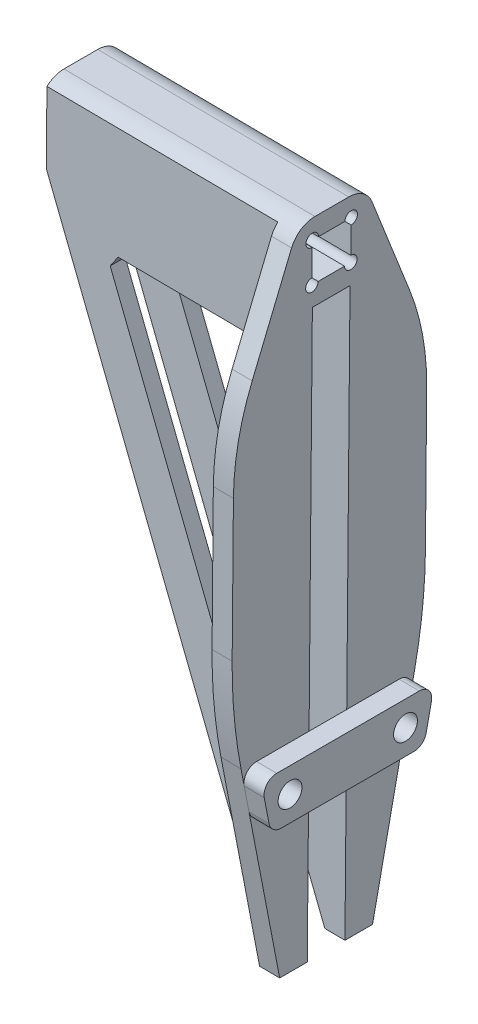
SolidWorks part; units mm, degrees
material "Onyx (Density Only)"
ref_plane "Front Plane" through (0, 0, 0) normal (0, 0, 1) x (1, 0, 0)
ref_plane "Top Plane" through (0, 0, 0) normal (0, 1, 0) x (1, 0, 0)
ref_plane "Right Plane" through (0, 0, 0) normal (1, 0, 0) x (0, 0, -1)
sketch "Sketch1" plane through (0, 0, 0) normal (0, 0, 1) x (1, 0, 0)
  line L0 (-62.6619, -20.8427) -> (-62.2163, 29.2053) construction
  line L1 (-354.9943, -0.7157) -> (-354.7319, 28.7594) construction
  line L2 (-269.9976, -1.4725) -> (-354.9943, -0.7157) construction
  line L3 (-269.9976, -1.4725) -> (-269.7352, 28.0027) construction
  line L4 (-322.9314, 6.2004) -> (-301.9323, 6.0134)
  line L5 (-301.9323, 6.0134) -> (-301.7693, 24.3127)
  line L6 (-301.7693, 24.3127) -> (-322.7685, 24.4997)
  line L7 (-322.7685, 24.4997) -> (-322.9314, 6.2004)
  line L8 (-322.9314, 6.2004) -> (-301.9323, 6.0134)
  line L9 (-301.9323, 6.0134) -> (-301.7693, 24.3127)
  line L10 (-301.7693, 24.3127) -> (-322.7685, 24.4997)
  line L11 (-322.7685, 24.4997) -> (-322.9314, 6.2004)
  line L12 (-371.7271, 31.9358) -> (-371.7538, 28.9359)
  line L13 (-82.6905, -23.6645) -> (-52.6917, -23.9316)
  line L14 (-52.6917, -23.9316) -> (-52.2466, 26.0664)
  line L15 (-52.2466, 26.0664) -> (-371.754, 28.9109)
  line L16 (-386.1059, -102.4513) -> (-381.2798, -121.0102)
  line L17 (-381.2798, -121.0102) -> (-173.5772, -122.8594)
  line L18 (-82.6905, -23.6645) -> (-52.6917, -23.9316)
  line L19 (-52.6917, -23.9316) -> (-52.2466, 26.0664)
  line L20 (-52.2466, 26.0664) -> (-371.754, 28.9109)
  line L21 (-386.1059, -102.4513) -> (-381.2798, -121.0102)
  line L22 (-381.2798, -121.0102) -> (-173.5772, -122.8594)
  line L23 (-371.7538, 28.9359) -> (-39.2441, 25.9756)
  line L24 (-39.2441, 25.9756) -> (-39.2174, 28.9755)
  line L25 (-39.2174, 28.9755) -> (-371.7271, 31.9358)
  line L26 (-371.7271, 31.9358) -> (-371.7538, 28.9359)
  line L27 (-371.7538, 28.9359) -> (-39.2441, 25.9756)
  line L28 (-39.2441, 25.9756) -> (-39.2174, 28.9755)
  line L29 (-39.2174, 28.9755) -> (-371.7271, 31.9358)
  line L30 (-62.6619, -20.8427) -> (-62.2163, 29.2053)
  line L31 (-354.9943, -0.7157) -> (-354.7319, 28.7594)
  line L32 (-269.9976, -1.4725) -> (-354.9943, -0.7157)
  line L33 (-269.9976, -1.4725) -> (-269.7352, 28.0027)
  spline S2 degree 3 poles (2410.225, -2834.3979) (-3146.448, 3563.7765) (2149.655, -3851.3111) (-2597.6592, 3230.2911) knots -1.52414 -1.52414 -1.52414 -1.52414 2.993571 2.993571 2.993571 2.993571 only from (-371.754, 28.9109) to (-386.1059, -102.4513)
  spline S3 degree 3 poles (-3364.9121, 2272.6683) (2814.1163, -2932.1633) (-3073.4881, 2782.8746) (3112.8833, -2413.4756) knots -2.734847 -2.734847 -2.734847 -2.734847 3.726468 3.726468 3.726468 3.726468 only from (-173.5772, -122.8594) to (-82.6905, -23.6645)
  spline S4 degree 3 poles (-371.754, 28.9109) (-424.0354, 24.6168) (-396.3089, -63.2154) (-386.1059, -102.4513) knots 0.202862 0.202862 0.202862 0.202862 0.957857 0.957857 0.957857 0.957857
  spline S5 degree 3 poles (-173.5772, -122.8594) (-128.8291, -103.0455) (-128.3643, -43.0034) (-82.6905, -23.6645) knots 0 0 0 0 1 1 1 1
  dimension "D1" = 0
  dimension "D2" = 0
  dimension "D3" = 0
sketch "Sketch2" plane through (0, 0, 0) normal (0, 0, 1) x (1, 0, 0)
  line L0 (-62.6619, -20.8427) -> (-62.2163, 29.2053) construction
  line L1 (-354.9943, -0.7157) -> (-354.7319, 28.7594) construction
  line L2 (-269.9976, -1.4725) -> (-354.9943, -0.7157) construction
  line L3 (-269.9976, -1.4725) -> (-269.7352, 28.0027) construction
  line L4 (-322.9314, 6.2004) -> (-301.9323, 6.0134)
  line L5 (-82.6905, -23.6645) -> (-52.6917, -23.9316)
  line L6 (-52.6917, -23.9316) -> (-52.2466, 26.0664)
  line L7 (-52.2466, 26.0664) -> (-371.754, 28.9109)
  line L8 (-386.1059, -102.4513) -> (-381.2798, -121.0102)
  line L9 (-381.2798, -121.0102) -> (-173.5772, -122.8594)
  line L10 (-82.6905, -23.6645) -> (-52.6917, -23.9316) construction
  line L11 (-52.6917, -23.9316) -> (-52.2466, 26.0664) construction
  line L12 (-52.2466, 26.0664) -> (-371.754, 28.9109) construction
  line L13 (-386.1059, -102.4513) -> (-381.2798, -121.0102) construction
  line L14 (-381.2798, -121.0102) -> (-173.5772, -122.8594) construction
  line L15 (-301.9323, 6.0134) -> (-301.7693, 24.3127)
  line L16 (-301.7693, 24.3127) -> (-322.7685, 24.4997)
  line L17 (-322.7685, 24.4997) -> (-322.9314, 6.2004)
  line L18 (-322.9314, 6.2004) -> (-301.9323, 6.0134) construction
  line L19 (-301.9323, 6.0134) -> (-301.7693, 24.3127) construction
  line L20 (-301.7693, 24.3127) -> (-322.7685, 24.4997) construction
  line L21 (-322.7685, 24.4997) -> (-322.9314, 6.2004) construction
  line L22 (-39.2441, 25.9756) -> (-39.2174, 28.9755)
  line L23 (-371.7538, 28.9359) -> (-39.2441, 25.9756)
  line L24 (-371.7271, 31.9358) -> (-371.7538, 28.9359)
  line L25 (-39.2174, 28.9755) -> (-371.7271, 31.9358)
  line L26 (-39.2441, 25.9756) -> (-39.2174, 28.9755) construction
  line L27 (-371.7538, 28.9359) -> (-39.2441, 25.9756) construction
  line L28 (-371.7271, 31.9358) -> (-371.7538, 28.9359) construction
  line L29 (-39.2174, 28.9755) -> (-371.7271, 31.9358) construction
  line L30 (-62.6619, -20.8427) -> (-62.2163, 29.2053) construction
  line L31 (-354.9943, -0.7157) -> (-354.7319, 28.7594) construction
  line L32 (-269.9976, -1.4725) -> (-354.9943, -0.7157) construction
  line L33 (-269.9976, -1.4725) -> (-269.7352, 28.0027) construction
  line L34 (-159.2127, 30.0438) -> (-159.6578, -19.9562)
  spline S2 degree 3 poles (3711.5688, -4352.7198) (-4405.7996, 5221.6724) (3347.4946, -5555.5394) (-3714.769, 4889.0268) knots -1.833594 -1.833594 -1.833594 -1.833594 3.301446 3.301446 3.301446 3.301446 only from (-371.754, 28.9109) to (-386.1059, -102.4513)
  spline S3 degree 3 poles (-4888.4094, 3568.1658) (4295.8794, -4300.758) (-4555.8185, 4150.8213) (4638.0833, -3707.0277) knots -3.19796 -3.19796 -3.19796 -3.19796 4.189584 4.189584 4.189584 4.189584 only from (-173.5772, -122.8594) to (-82.6905, -23.6645)
  spline S4 degree 3 poles (-371.754, 28.9109) (-424.0354, 24.6168) (-396.3089, -63.2154) (-386.1059, -102.4513) knots 0.202862 0.202862 0.202862 0.202862 0.957857 0.957857 0.957857 0.957857 construction
  spline S5 degree 3 poles (-173.5772, -122.8594) (-128.8291, -103.0455) (-128.3643, -43.0034) (-82.6905, -23.6645) knots 0 0 0 0 1 1 1 1 construction
  dimension "D4" = 120
  dimension "D5" = 50
  dimension "D1" = 0
  dimension "D2" = 0
  dimension "D3" = 0
sketch "Sketch3" plane through (0, 0, 0) normal (0, 0, 1) x (1, 0, 0)
  line L0 (-159.2127, 30.0438) -> (-159.6578, -19.9562) construction
  line L1 (-159.2127, 30.0438) -> (-159.6578, -19.9562)
  line L2 (-169.2123, 30.1329) -> (-169.6574, -19.8671)
  line L3 (-149.2131, 29.9548) -> (-149.6582, -20.0452)
  line L4 (-149.2131, 29.9548) -> (-169.2123, 30.1329)
  line L5 (-149.6582, -20.0452) -> (-169.6574, -19.8671)
  line L6 (-149.2131, 29.9548) -> (-149.1988, 31.5547)
  line L7 (-149.1988, 31.5547) -> (-169.198, 31.7328)
  line L8 (-169.198, 31.7328) -> (-169.2123, 30.1329)
  dimension "D3" = 1.6
  dimension "D1" = 10
  dimension "D2" = 10
extrude "Boss-Extrude1" add sketch "Sketch3" along normal mid plane 3 contours L5 L3 L4 L1 | L5 L1 L4 L2 | L7 L8 L4 L6
sketch "Sketch4" plane through (0, 0, 0) normal (0, 0, 1) x (1, 0, 0)
  line L0 (-169.2123, 30.1329) -> (-169.6574, -19.8671) construction
  line L1 (-149.6582, -20.0452) -> (-169.6574, -19.8671) construction
  line L2 (-149.2131, 29.9548) -> (-149.6582, -20.0452) construction
  line L3 (-149.2131, 29.9548) -> (-169.2123, 30.1329) construction
  line L4 (-149.2131, 29.9548) -> (-149.1988, 31.5547) construction
  line L5 (-149.1988, 31.5547) -> (-169.198, 31.7328) construction
  line L6 (-169.198, 31.7328) -> (-169.2123, 30.1329) construction
  line L7 (-159.2127, 30.0438) -> (-159.6578, -19.9562) construction
  line L8 (-169.2123, 30.1329) -> (-169.6574, -19.8671)
  line L9 (-149.6582, -20.0452) -> (-169.6574, -19.8671)
  line L10 (-149.2131, 29.9548) -> (-149.6582, -20.0452)
  line L11 (-149.2131, 29.9548) -> (-169.2123, 30.1329)
  line L12 (-149.2131, 29.9548) -> (-149.1988, 31.5547)
  line L13 (-149.1988, 31.5547) -> (-169.198, 31.7328)
  line L14 (-169.198, 31.7328) -> (-169.2123, 30.1329)
  line L15 (-159.2127, 30.0438) -> (-159.6578, -19.9562)
extrude "Boss-Extrude2" add sketch "Sketch4" along normal offset from surface 1.2 and the other way offset from surface (2.7 mm away) 1.2 contours L11 L15 L9 L10 | L15 L11 L8 L9 | L13 L14 L11 L12 up to face at (-159.4281, 5.8438, 1.5) offset beyond the face yes
sketch "Sketch5" plane through (0, 0, 0) normal (0, 0, 1) x (1, 0, 0)
  line L0 (-52.2466, 26.0664) -> (-371.754, 28.9109) construction
  line L1 (-52.2466, 26.0664) -> (-371.754, 28.9109)
  line L2 (-52.2608, 24.4665) -> (-371.7683, 27.311)
  line L6 (-149.6582, -20.0452) -> (-149.1988, 31.5547)
  line L7 (-149.1988, 31.5547) -> (-169.198, 31.7328)
  line L8 (-169.198, 31.7328) -> (-169.6574, -19.8671)
  line L9 (-169.6574, -19.8671) -> (-149.6582, -20.0452)
  line L10 (-149.6582, -20.0452) -> (-149.1988, 31.5547)
  line L11 (-149.1988, 31.5547) -> (-169.198, 31.7328)
  line L12 (-169.198, 31.7328) -> (-169.6574, -19.8671)
  line L13 (-169.6574, -19.8671) -> (-149.6582, -20.0452)
  dimension "D1" = 0
  dimension "D2" = 1.6
extrude "Cut-Extrude1" cut sketch "Sketch5" against normal mid plane 3 contours L12 L13 L10 L1
ref_plane "Plane1" through (-149.4679, 1.3307, 0) normal (1, -0.0089, 0) x (0, 0, -1)
sketch "Sketch6" plane through (-149.4679, 1.3307, 0) normal (1, -0.0089, 0) x (0, 0, -1)
  line L0 (2.7, 30.2253) -> (7.7, 17.7253)
  line L1 (7.7, 17.7253) -> (7.7, -21.3767)
  line L2 (7.7, -21.3767) -> (2.7, -21.3767)
  line L3 (0, 30.2253) -> (0, 24.0003) construction
  line L4 (-7.7, -21.3767) -> (-2.7, -21.3767)
  line L5 (-7.7, 17.7253) -> (-7.7, -21.3767)
  line L6 (-2.7, 30.2253) -> (-7.7, 17.7253)
  line L8 (-1.5, 24.0003) -> (1.5, 24.0003)
  line L9 (1.5, 24.0003) -> (1.5, -21.3767)
  line L10 (1.5, -21.3767) -> (2.7, -21.3767)
  line L11 (2.7, -21.3767) -> (2.7, 30.2253)
  line L12 (2.7, 30.2253) -> (-2.7, 30.2253)
  line L13 (-2.7, 30.2253) -> (-2.7, -21.3767)
  line L14 (-2.7, -21.3767) -> (-1.5, -21.3767)
  line L15 (-1.5, -21.3767) -> (-1.5, 24.0003)
  line L16 (-1.5, 24.0003) -> (1.5, 24.0003)
  line L17 (1.5, 24.0003) -> (1.5, -21.3767)
  line L18 (1.5, -21.3767) -> (2.7, -21.3767)
  line L19 (2.7, -21.3767) -> (2.7, 30.2253)
  line L20 (2.7, 30.2253) -> (-2.7, 30.2253)
  line L21 (-2.7, 30.2253) -> (-2.7, -21.3767)
  line L22 (-2.7, -21.3767) -> (-1.5, -21.3767)
  line L23 (-1.5, -21.3767) -> (-1.5, 24.0003)
  dimension "D2" = 12.5
  dimension "D3" = 5
  dimension "D1" = 0
extrude "Boss-Extrude3" add sketch "Sketch6" against normal blind 1.6 contours L21 L6 L5 L4 | L19 L2 L1 L0
sketch "Sketch7" plane through (0, 0, 0) normal (0, 0, 1) x (1, 0, 0)
  line L0 (-169.2534, 25.508) -> (-151.2581, -20.031)
  line L4 (-169.2534, 25.508) -> (-169.6574, -19.8671)
  line L5 (-169.6574, -19.8671) -> (-149.6582, -20.0452)
  line L6 (-149.6582, -20.0452) -> (-149.2542, 25.33)
  line L7 (-149.2542, 25.33) -> (-169.2534, 25.508)
  line L8 (-169.2534, 25.508) -> (-169.6574, -19.8671)
  line L9 (-169.6574, -19.8671) -> (-149.6582, -20.0452)
  line L10 (-149.6582, -20.0452) -> (-149.2542, 25.33)
  line L11 (-149.2542, 25.33) -> (-169.2534, 25.508)
  line L12 (-149.6582, -20.0452) -> (-149.3101, 19.0552)
  line L13 (-149.3101, 19.0552) -> (-150.91, 19.0695)
  line L14 (-150.91, 19.0695) -> (-151.2581, -20.031)
  line L15 (-151.2581, -20.031) -> (-149.6582, -20.0452)
  line L16 (-149.6582, -20.0452) -> (-149.3101, 19.0552)
  line L17 (-149.3101, 19.0552) -> (-150.91, 19.0695)
  line L18 (-150.91, 19.0695) -> (-151.2581, -20.031)
  line L19 (-151.2581, -20.031) -> (-149.6582, -20.0452)
  dimension "D1" = 0
  dimension "D2" = 0
extrude "Cut-Extrude2" cut sketch "Sketch7" against normal through all both and the other way through all contours L8 L9 L0
sketch "Sketch8" plane through (0, 0, 0) normal (0, 0, 1) x (1, 0, 0)
  line L1 (-371.7271, 31.9358) -> (-371.7538, 28.9359) construction
  line L2 (-52.2466, 26.0664) -> (-371.754, 28.9109) construction
  line L3 (-39.2174, 28.9755) -> (-371.7271, 31.9358) construction
  line L4 (-39.2441, 25.9756) -> (-39.2174, 28.9755) construction
  line L5 (-371.7271, 31.9358) -> (-371.7538, 28.9359)
  line L6 (-52.2466, 26.0664) -> (-371.754, 28.9109)
  line L7 (-39.2174, 28.9755) -> (-371.7271, 31.9358)
  line L8 (-371.7538, 28.9359) -> (-39.2441, 25.9756) construction
  line L9 (-39.2441, 25.9756) -> (-39.2174, 28.9755)
  line L10 (-371.7538, 28.9359) -> (-39.2441, 25.9756)
extrude "Cut-Extrude3" cut sketch "Sketch8" against normal mid plane 3 contours L5 L10 L9 L7
sketch "Sketch9" plane through (-149.4679, 1.3307, 0) normal (1, -0.0089, 0) x (0, 0, -1)
  line L0 (1.55, 28.6753) -> (-1.55, 28.6753)
  line L1 (-1.55, 28.6753) -> (-1.55, 25.5753)
  line L2 (-1.55, 25.5753) -> (1.55, 25.5753)
  line L3 (1.55, 25.5753) -> (1.55, 28.6753)
  line L4 (1.5, 28.6253) -> (-1.5, 28.6253)
  line L5 (1.5, 25.6253) -> (1.5, 28.6253)
  line L6 (-1.5, 25.6253) -> (1.5, 25.6253)
  line L7 (-1.5, 28.6253) -> (-1.5, 25.6253)
  line L8 (1.5, 28.6253) -> (-1.5, 28.6253)
  line L9 (1.5, 25.6253) -> (1.5, 28.6253)
  line L10 (-1.5, 25.6253) -> (1.5, 25.6253)
  line L11 (-1.5, 28.6253) -> (-1.5, 25.6253)
  dimension "D1" = 0
  dimension "D2" = 0.05
extrude "Cut-Extrude4" cut sketch "Sketch9" against normal through all
sketch "Sketch10" plane through (-149.4679, 1.3307, 0) normal (1, -0.0089, 0) x (0, 0, -1)
  line L4 (1.55, 25.5753) -> (1.55, 28.6753)
  line L5 (-1.55, 25.5753) -> (1.55, 25.5753)
  line L6 (-1.55, 28.6753) -> (-1.55, 25.5753)
  line L7 (1.55, 28.6753) -> (-1.55, 28.6753)
  line L8 (1.55, 25.5753) -> (1.55, 28.6753) construction
  line L9 (-1.55, 25.5753) -> (1.55, 25.5753) construction
  line L10 (-1.55, 28.6753) -> (-1.55, 25.5753) construction
  line L11 (1.55, 28.6753) -> (-1.55, 28.6753) construction
  circle A0 centre (-1.55, 25.5753) radius 0.5
  circle A1 centre (1.55, 25.5753) radius 0.5
  circle A2 centre (-1.55, 28.6753) radius 0.5
  circle A3 centre (1.55, 28.6753) radius 0.5
  dimension "D2" = 1
  dimension "D3" = 1
  dimension "D4" = 1
  dimension "D5" = 1
  dimension "D1" = 0
extrude "Cut-Extrude5" cut sketch "Sketch10" against normal through all
sketch "Sketch11" plane through (-149.4679, 1.3307, 0) normal (1, -0.0089, 0) x (0, 0, -1)
  line L10 (-1.5, 24.0003) -> (1.5, 24.0003)
  line L11 (1.5, 24.0003) -> (1.5, -21.3767)
  line L12 (1.5, -21.3767) -> (7.7, -21.3767)
  line L13 (7.7, -21.3767) -> (7.7, 17.7253)
  line L14 (7.7, 17.7253) -> (2.7, 30.2253)
  line L15 (2.7, 30.2253) -> (-2.7, 30.2253)
  line L16 (-2.7, 30.2253) -> (-7.7, 17.7253)
  line L17 (-7.7, 17.7253) -> (-7.7, -21.3767)
  line L18 (-7.7, -21.3767) -> (-1.5, -21.3767)
  line L19 (-1.5, -21.3767) -> (-1.5, 24.0003)
  line L20 (-1.5, 24.0003) -> (1.5, 24.0003)
  line L21 (1.5, 24.0003) -> (1.5, -21.3767)
  line L22 (1.5, -21.3767) -> (7.7, -21.3767)
  line L23 (7.7, -21.3767) -> (7.7, 17.7253)
  line L24 (7.7, 17.7253) -> (3.2029, 28.968)
  line L25 (1.3459, 30.2253) -> (-1.3459, 30.2253)
  line L26 (-3.2029, 28.968) -> (-7.7, 17.7253)
  line L27 (-7.7, 17.7253) -> (-7.7, -21.3767)
  line L28 (-7.7, -21.3767) -> (-1.5, -21.3767)
  line L29 (-1.5, -21.3767) -> (-1.5, 24.0003)
  arc A0 (3.2029, 28.968) -> (1.3459, 30.2253) centre (1.3459, 28.2253) ccw
  arc A1 (-1.3459, 30.2253) -> (-3.2029, 28.968) centre (-1.3459, 28.2253) ccw
  dimension "D2" = 2
  dimension "D1" = 0
sketch "Sketch12" plane through (-149.4679, 1.3307, 0) normal (1, -0.0089, 0) x (0, 0, -1)
  line L10 (-1.5, 24.0003) -> (1.5, 24.0003)
  line L11 (1.5, 24.0003) -> (1.5, -21.3767)
  line L12 (1.5, -21.3767) -> (7.7, -21.3767)
  line L13 (7.7, -21.3767) -> (7.7, 17.7253)
  line L14 (7.7, 17.7253) -> (2.7, 30.2253)
  line L15 (2.7, 30.2253) -> (-2.7, 30.2253)
  line L16 (-2.7, 30.2253) -> (-7.7, 17.7253)
  line L17 (-7.7, 17.7253) -> (-7.7, -21.3767)
  line L18 (-7.7, -21.3767) -> (-1.5, -21.3767)
  line L19 (-1.5, -21.3767) -> (-1.5, 24.0003)
  line L20 (-1.5, 24.0003) -> (1.5, 24.0003)
  line L21 (1.5, 24.0003) -> (1.5, -21.3767)
  line L22 (1.5, -21.3767) -> (7.7, -21.3767)
  line L23 (7.7, -21.3767) -> (7.7, 17.7253)
  line L24 (7.7, 17.7253) -> (2.7, 30.2253)
  line L25 (2.7, 30.2253) -> (-2.7, 30.2253)
  line L26 (-2.7, 30.2253) -> (-7.7, 17.7253)
  line L27 (-7.7, 17.7253) -> (-7.7, -21.3767)
  line L28 (-7.7, -21.3767) -> (-1.5, -21.3767)
  line L29 (-1.5, -21.3767) -> (-1.5, 24.0003)
  line L30 (-7.7, -21.3767) -> (-1.5, -21.3767)
  line L31 (-7.7, 17.7253) -> (-7.7, -21.3767)
  line L32 (-3.2029, 28.968) -> (-7.7, 17.7253)
  line L33 (1.3459, 30.2253) -> (-1.3459, 30.2253)
  line L34 (7.7, 17.7253) -> (3.2029, 28.968)
  line L35 (7.7, -21.3767) -> (7.7, 17.7253)
  line L36 (1.5, -21.3767) -> (7.7, -21.3767)
  line L37 (1.5, 24.0003) -> (1.5, -21.3767)
  line L38 (-1.5, 24.0003) -> (1.5, 24.0003)
  line L39 (-1.5, -21.3767) -> (-1.5, 24.0003)
  line L40 (-7.7, -21.3767) -> (-1.5, -21.3767)
  line L41 (-7.7, 17.7253) -> (-7.7, -21.3767)
  line L42 (-3.2029, 28.968) -> (-7.7, 17.7253)
  line L43 (1.3459, 30.2253) -> (-1.3459, 30.2253)
  line L44 (7.7, 17.7253) -> (3.2029, 28.968)
  line L45 (7.7, -21.3767) -> (7.7, 17.7253)
  line L46 (1.5, -21.3767) -> (7.7, -21.3767)
  line L47 (1.5, 24.0003) -> (1.5, -21.3767)
  line L48 (-1.5, 24.0003) -> (1.5, 24.0003)
  line L49 (-1.5, -21.3767) -> (-1.5, 24.0003)
  arc A2 (-1.3459, 30.2253) -> (-3.2029, 28.968) centre (-1.3459, 28.2253) ccw
  arc A3 (3.2029, 28.968) -> (1.3459, 30.2253) centre (1.3459, 28.2253) ccw
  arc A4 (-1.3459, 30.2253) -> (-3.2029, 28.968) centre (-1.3459, 28.2253) ccw
  arc A5 (3.2029, 28.968) -> (1.3459, 30.2253) centre (1.3459, 28.2253) ccw
  dimension "D1" = 0
  dimension "D2" = 0
extrude "Cut-Extrude6" cut sketch "Sketch12" against normal through all contours A4 L25 L26 | A5 L24 L25
fillet "Fillet1" radius 20 2 edges at (-150.1101, 19.0624, -7.7) (-150.1101, 19.0624, 7.7)
sketch "Sketch13" plane through (-149.4679, 1.3307, 0) normal (1, -0.0089, 0) x (0, 0, -1)
  line L0 (3.2029, 28.968) -> (6.2695, 21.3014) construction
  line L1 (7.7, 13.8736) -> (7.7, -21.3767) construction
  line L2 (7.7, -21.3767) -> (2.7, -21.3767) construction
  line L3 (2.7, -21.3767) -> (2.7, 29.6972) construction
  line L4 (-7.7, -21.3767) -> (-7.7, 13.8736) construction
  line L5 (-6.2695, 21.3014) -> (-3.2029, 28.968) construction
  line L6 (-2.7, 29.6972) -> (-2.7, -21.3767) construction
  line L7 (-2.7, -21.3767) -> (-7.7, -21.3767) construction
  line L8 (3.2029, 28.968) -> (6.2695, 21.3014)
  line L9 (7.7, 13.8736) -> (7.7, -21.3767)
  line L10 (7.7, -21.3767) -> (2.7, -21.3767)
  line L11 (2.7, -21.3767) -> (2.7, 29.6972)
  line L12 (-7.7, -21.3767) -> (-7.7, 13.8736)
  line L13 (-6.2695, 21.3014) -> (-3.2029, 28.968)
  line L14 (-2.7, 29.6972) -> (-2.7, -21.3767)
  line L15 (-2.7, -21.3767) -> (-7.7, -21.3767)
  line L16 (-3.7, -21.3767) -> (-7.7, -1.3767)
  line L17 (-2.7, -21.3767) -> (2.7, -21.3767) construction
  line L18 (0, -21.3767) -> (0, -11.4952) construction
  line L19 (3.7, -21.3767) -> (7.7, -1.3767)
  arc A0 (7.7, 13.8736) -> (6.2695, 21.3014) centre (-12.3, 13.8736) ccw construction
  arc A1 (3.2029, 28.968) -> (2.7, 29.6972) centre (1.3459, 28.2253) ccw construction
  arc A2 (-6.2695, 21.3014) -> (-7.7, 13.8736) centre (12.3, 13.8736) ccw construction
  arc A3 (-2.7, 29.6972) -> (-3.2029, 28.968) centre (-1.3459, 28.2253) ccw construction
  arc A4 (7.7, 13.8736) -> (6.2695, 21.3014) centre (-12.3, 13.8736) ccw
  arc A5 (3.2029, 28.968) -> (2.7, 29.6972) centre (1.3459, 28.2253) ccw
  arc A6 (-6.2695, 21.3014) -> (-7.7, 13.8736) centre (12.3, 13.8736) ccw
  arc A7 (-2.7, 29.6972) -> (-3.2029, 28.968) centre (-1.3459, 28.2253) ccw
  dimension "D1" = 1
  dimension "D2" = 20
extrude "Cut-Extrude7" cut sketch "Sketch13" against normal through all contours L15 L16 L12 | L19 L10 L9
fillet "Fillet2" radius 40 2 edges at (-150.2801, -0.0389, -7.7) (-150.2801, -0.0389, 7.7)
sketch "Sketch14" plane through (-149.4679, 1.3307, 0) normal (1, -0.0089, 0) x (0, 0, -1)
  line L0 (7.7, 13.8736) -> (7.7, 2.5841) construction
  line L1 (6.9232, -5.2606) -> (3.7, -21.3767) construction
  line L2 (3.7, -21.3767) -> (2.7, -21.3767) construction
  line L3 (2.7, -21.3767) -> (2.7, 29.6972) construction
  line L4 (3.2029, 28.968) -> (6.2695, 21.3014) construction
  line L5 (-3.7, -21.3767) -> (-6.9232, -5.2606) construction
  line L6 (-7.7, 2.5841) -> (-7.7, 13.8736) construction
  line L7 (-6.2695, 21.3014) -> (-3.2029, 28.968) construction
  line L8 (-2.7, 29.6972) -> (-2.7, -21.3767) construction
  line L9 (-2.7, -21.3767) -> (-3.7, -21.3767) construction
  line L10 (7.7, 13.8736) -> (7.7, 2.5841)
  line L11 (6.9232, -5.2606) -> (3.7, -21.3767)
  line L12 (3.7, -21.3767) -> (6.9232, -5.2606)
  line L13 (7.7, 2.5841) -> (7.7, 13.8736)
  line L14 (6.2695, 21.3014) -> (3.2029, 28.968)
  line L15 (1.3459, 30.2253) -> (-1.3459, 30.2253)
  line L16 (-3.2029, 28.968) -> (-6.2695, 21.3014)
  line L17 (-7.7, 13.8736) -> (-7.7, 2.5841)
  line L18 (-6.9232, -5.2606) -> (-3.7, -21.3767)
  line L19 (-3.7, -21.3767) -> (-1.5, -21.3767)
  line L20 (-1.5, -21.3767) -> (-1.5, 24.0003)
  line L21 (-1.5, 24.0003) -> (1.5, 24.0003)
  line L22 (1.5, 24.0003) -> (1.5, -21.3767)
  line L23 (1.5, -21.3767) -> (3.7, -21.3767)
  line L24 (3.7, -21.3767) -> (6.9232, -5.2606)
  line L25 (7.7, 2.5841) -> (7.7, 13.8736)
  line L26 (6.2695, 21.3014) -> (3.2029, 28.968)
  line L27 (1.3459, 30.2253) -> (-1.3459, 30.2253)
  line L28 (-3.2029, 28.968) -> (-6.2695, 21.3014)
  line L29 (-7.7, 13.8736) -> (-7.7, 2.5841)
  line L30 (-6.9232, -5.2606) -> (-3.7, -21.3767)
  line L31 (-3.7, -21.3767) -> (-1.5, -21.3767)
  line L32 (-1.5, -21.3767) -> (-1.5, 24.0003)
  line L33 (-1.5, 24.0003) -> (1.5, 24.0003)
  line L34 (1.5, 24.0003) -> (1.5, -21.3767)
  line L35 (1.5, -21.3767) -> (3.7, -21.3767)
  line L36 (3.7, -21.3767) -> (2.7, -21.3767)
  line L37 (2.7, -21.3767) -> (2.7, 29.6972)
  line L38 (3.2029, 28.968) -> (6.2695, 21.3014)
  line L39 (-3.7, -21.3767) -> (-6.9232, -5.2606)
  line L40 (-7.7, 2.5841) -> (-7.7, 13.8736)
  line L41 (-6.2695, 21.3014) -> (-3.2029, 28.968)
  line L42 (-2.7, 29.6972) -> (-2.7, -21.3767)
  line L43 (-2.7, -21.3767) -> (-3.7, -21.3767)
  line L44 (-6.5, -7.3767) -> (-2.7, -7.3767) construction
  line L45 (-3.7, -21.3767) -> (-6.9232, -5.2606) construction
  line L46 (-1.5, -21.3767) -> (1.5, -21.3767) construction
  line L47 (0, -21.3767) -> (0, -7.3767) construction
  line L48 (-6.5, -7.3767) -> (6.5, -7.3767) construction
  line L49 (-6.5, -9.3767) -> (6.5, -9.3767)
  line L50 (-6.9, -5.3767) -> (6.9, -5.3767)
  line L51 (-6.5, -5.3767) -> (6.5, -5.3767) construction
  arc A0 (6.9232, -5.2606) -> (7.7, 2.5841) centre (-32.3, 2.5841) ccw construction
  arc A1 (3.2029, 28.968) -> (2.7, 29.6972) centre (1.3459, 28.2253) ccw construction
  arc A2 (7.7, 13.8736) -> (6.2695, 21.3014) centre (-12.3, 13.8736) ccw construction
  arc A3 (-7.7, 2.5841) -> (-6.9232, -5.2606) centre (32.3, 2.5841) ccw construction
  arc A4 (-6.2695, 21.3014) -> (-7.7, 13.8736) centre (12.3, 13.8736) ccw construction
  arc A5 (-2.7, 29.6972) -> (-3.2029, 28.968) centre (-1.3459, 28.2253) ccw construction
  arc A6 (6.9232, -5.2606) -> (7.7, 2.5841) centre (-32.3, 2.5841) ccw
  arc A7 (7.7, 13.8736) -> (6.2695, 21.3014) centre (-12.3, 13.8736) ccw
  arc A8 (3.2029, 28.968) -> (1.3459, 30.2253) centre (1.3459, 28.2253) ccw
  arc A9 (-1.3459, 30.2253) -> (-3.2029, 28.968) centre (-1.3459, 28.2253) ccw
  arc A10 (-6.2695, 21.3014) -> (-7.7, 13.8736) centre (12.3, 13.8736) ccw
  arc A11 (-7.7, 2.5841) -> (-6.9232, -5.2606) centre (32.3, 2.5841) ccw
  arc A12 (6.9232, -5.2606) -> (7.7, 2.5841) centre (-32.3, 2.5841) ccw
  arc A13 (7.7, 13.8736) -> (6.2695, 21.3014) centre (-12.3, 13.8736) ccw
  arc A14 (3.2029, 28.968) -> (1.3459, 30.2253) centre (1.3459, 28.2253) ccw
  arc A15 (-1.3459, 30.2253) -> (-3.2029, 28.968) centre (-1.3459, 28.2253) ccw
  arc A16 (-6.2695, 21.3014) -> (-7.7, 13.8736) centre (12.3, 13.8736) ccw
  arc A17 (-7.7, 2.5841) -> (-6.9232, -5.2606) centre (32.3, 2.5841) ccw
  arc A18 (6.9232, -5.2606) -> (7.7, 2.5841) centre (-32.3, 2.5841) ccw
  arc A19 (3.2029, 28.968) -> (2.7, 29.6972) centre (1.3459, 28.2253) ccw
  arc A20 (7.7, 13.8736) -> (6.2695, 21.3014) centre (-12.3, 13.8736) ccw
  arc A21 (-7.7, 2.5841) -> (-6.9232, -5.2606) centre (32.3, 2.5841) ccw
  arc A22 (-6.2695, 21.3014) -> (-7.7, 13.8736) centre (12.3, 13.8736) ccw
  arc A23 (-2.7, 29.6972) -> (-3.2029, 28.968) centre (-1.3459, 28.2253) ccw
  circle A24 centre (-4.6, -7.3767) radius 0.95
  circle A25 centre (4.6, -7.3767) radius 0.95
  dimension "D2" = 1.9
  dimension "D3" = 14
  dimension "D1" = 0
  dimension "D4" = 2
  dimension "D5" = 2
extrude "Boss-Extrude4" add sketch "Sketch14" along normal blind 1.6 separate body contours L50 L39 L49 L42 A24 | L50 L42 L49 L32 | L50 L32 L49 L34 | L50 L34 L49 L37 | L50 L37 L49 L24 A25
sketch "Sketch15" plane through (-149.4679, 1.3307, 0) normal (1, -0.0089, 0) x (0, 0, -1)
  circle A1 centre (-4.6, -7.3767) radius 0.95
  circle A2 centre (-4.6, -7.3767) radius 0.95
  circle A3 centre (4.6, -7.3767) radius 0.95
  circle A4 centre (4.6, -7.3767) radius 0.95
  dimension "D1" = 0
  dimension "D2" = 0
extrude "Cut-Extrude8" cut sketch "Sketch15" against normal through all
fillet "Fillet3" radius 1 4 edges at (-148.7158, -4.053, -6.9) (-148.7514, -8.0528, -6.1) (-148.7514, -8.0528, 6.1) (-148.7158, -4.053, 6.9)
sketch "Sketch16" plane through (0, 0, 0) normal (0, 0, 1) x (1, 0, 0)
  line L0 (-152.4826, 22.1586) -> (-164.5315, 22.2659)
  line L1 (-164.5315, 22.2659) -> (-152.7471, -7.5556)
  line L2 (-152.7471, -7.5556) -> (-152.7471, -7.5556)
  line L3 (-152.7471, -7.5556) -> (-152.4826, 22.1586)
  line L4 (-149.2542, 25.33) -> (-169.2534, 25.508)
  line L5 (-169.2534, 25.508) -> (-151.2581, -20.031)
  line L6 (-151.2581, -20.031) -> (-149.6582, -20.0452)
  line L7 (-149.6582, -20.0452) -> (-149.2542, 25.33)
  line L8 (-149.2542, 25.33) -> (-169.2534, 25.508)
  line L9 (-169.2534, 25.508) -> (-151.2581, -20.031)
  line L10 (-151.2581, -20.031) -> (-149.6582, -20.0452)
  line L11 (-149.6582, -20.0452) -> (-149.2542, 25.33)
  dimension "D1" = 0
  dimension "D2" = 3.2
extrude "Cut-Extrude9" cut sketch "Sketch16" against normal through all both and the other way through all contours L1 L3 L0
chamfer "Chamfer1" distance 1 6 edges at (-152.7471, -7.5556, -2.1) (-152.7471, -7.5556, 2.1) (-164.5315, 22.2659, 2.1) (-164.5315, 22.2659, -2.1) (-152.4826, 22.1586, -2.1) (-152.4826, 22.1586, 2.1)
